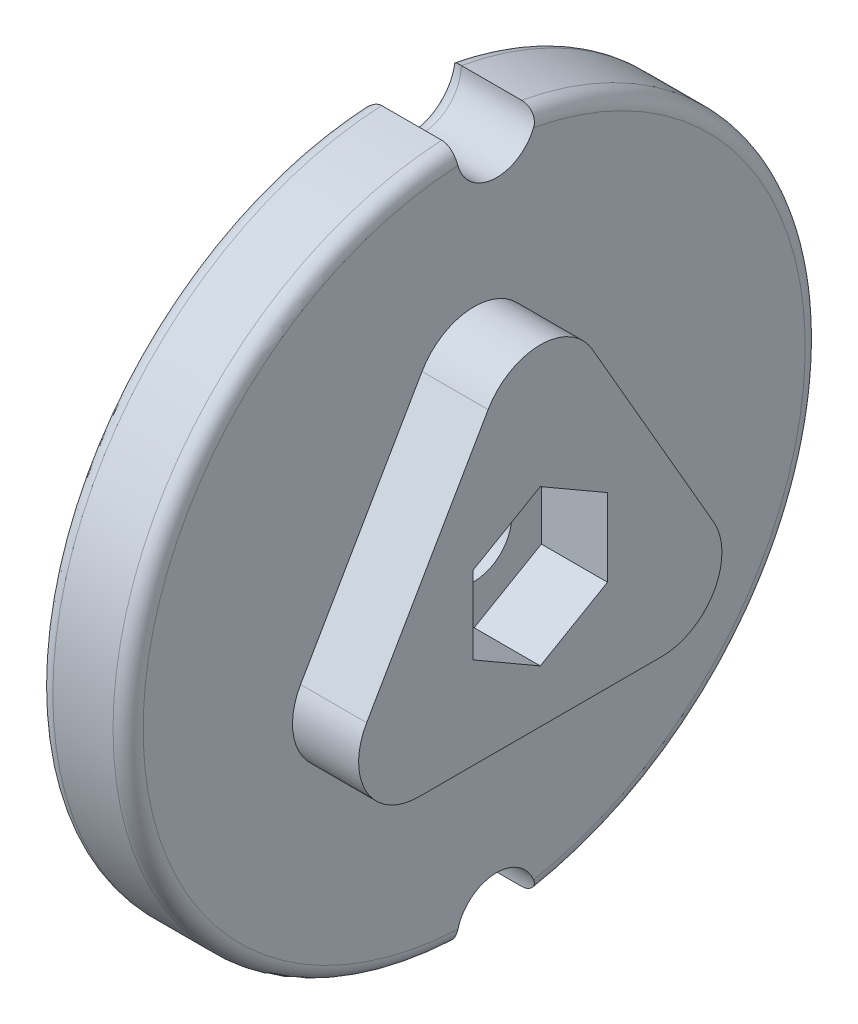
SolidWorks part; units mm, degrees
ref_plane "Front Plane" through (0, 0, 0) normal (0, 0, 1) x (1, 0, 0)
ref_plane "Top Plane" through (0, 0, 0) normal (0, 1, 0) x (1, 0, 0)
ref_plane "Right Plane" through (0, 0, 0) normal (1, 0, 0) x (0, 0, -1)
sketch "Sketch2" plane through (0, 0, 0) normal (1, 0, 0) x (0, 0, -1)
  line L0 (55, 0) -> (-55, 0) construction
  arc A0 (5.2728, -28.7301) -> (5.2728, 28.7301) centre (0, 0) ccw
  circle A1 centre (0, 0) radius 3.175
  arc A2 (-1.46, -29.1735) -> (5.2728, -28.7301) centre (1.895, -28.7775) cw
  arc A3 (-1.46, 29.1735) -> (5.2728, 28.7301) centre (1.895, 28.7775) ccw
  arc A4 (-1.46, 29.1735) -> (-1.46, -29.1735) centre (0, 0) ccw
  point P11 (0, 0)
  dimension "D1" = 58.42
  dimension "D2" = 6.35
extrude "Boss-Extrude1" add sketch "Sketch2" along normal blind 7.62
sketch "Sketch3" plane through (7.62, 0, 0) normal (1, 0, 0) x (0, 0, -1)
  line L0 (-5.675, 3.2765) -> (-5.675, -3.2765)
  line L1 (19.05, -10.9985) -> (0, 21.997)
  line L2 (0, 21.997) -> (-19.05, -10.9985)
  line L3 (-19.05, -10.9985) -> (19.05, -10.9985)
  line L4 (5.675, -3.2765) -> (5.675, 3.2765)
  line L5 (5.675, 3.2765) -> (0, 6.5529)
  line L6 (0, 6.5529) -> (-5.675, 3.2765)
  line L7 (-5.675, -3.2765) -> (0, -6.5529)
  line L8 (0, -6.5529) -> (5.675, -3.2765)
  circle A0 centre (0, 0) radius 10.9985 construction
  circle A1 centre (0, 0) radius 5.675 construction
  dimension "D1" = 11.35
  dimension "D2" = 38.1
extrude "Boss-Extrude2" add sketch "Sketch3" along normal blind 5.58
fillet "Fillet1" radius 5.08 3 edges at (10.41, -10.9985, -19.05) (10.41, 21.997, 0) (10.41, -10.9985, 19.05)
fillet "Fillet3" radius 1.27 7 edges at (7.62, 0, -29.21) (7.62, 0, 29.21) (0, 0, -3.175) (0, -25.4066, -1.673) (0, 0, -29.21) (0, 25.4066, -1.673) (0, 0, 29.21)
sketch "Sketch5" plane through (0, 0, 0) normal (-1, 0, 0) x (0, 0, 1)
  line L1 (-6.2765, 27.2259) -> (1.7182, 27.2259)
  line L2 (-6.2765, 27.2259) -> (-6.2765, 25.412)
  line L3 (-6.2765, 25.412) -> (1.7182, 25.412)
  line L4 (1.7182, 27.2259) -> (1.7182, 25.412)
  arc A0 (-6.2765, 27.2259) -> (-6.2765, -27.2259) centre (0, 0) ccw construction
  arc A1 (-6.2765, 27.2259) -> (2.6522, 27.8138) centre (-1.895, 28.7775) ccw construction
